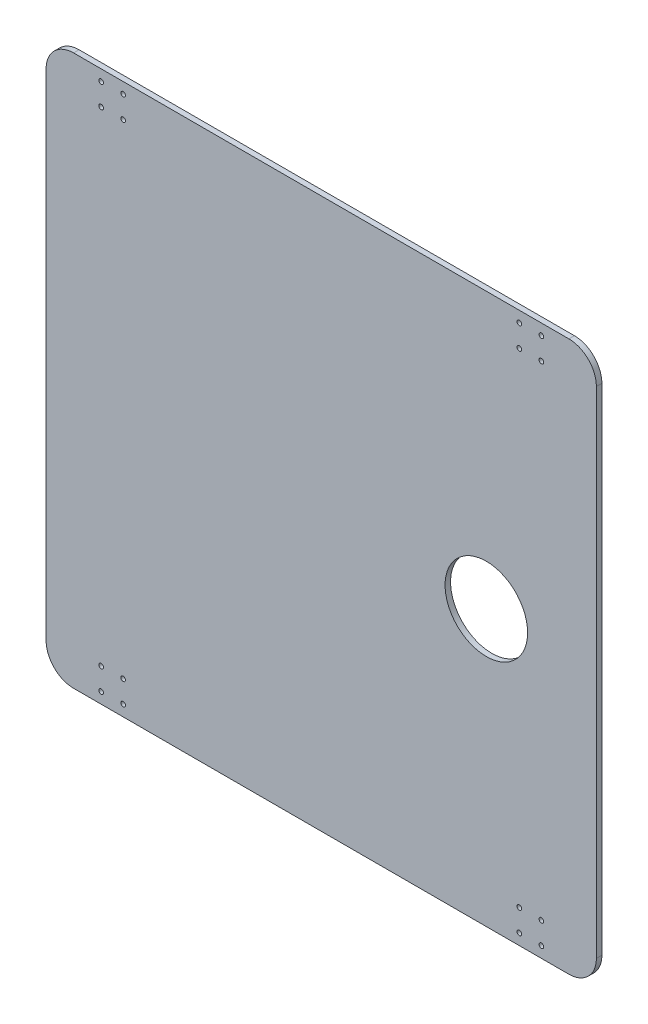
SolidWorks part; units mm, degrees
ref_plane "前视基准面" through (0, 0, 0) normal (0, 0, 1) x (1, 0, 0)
ref_plane "上视基准面" through (0, 0, 0) normal (0, 1, 0) x (1, 0, 0)
ref_plane "右视基准面" through (0, 0, 0) normal (1, 0, 0) x (0, 0, -1)
other "Configuration Table"
sketch "草图1" plane through (0, 0, 0) normal (0, 0, 1) x (1, 0, 0)
  line L0 (-492.228, -500) -> (1922.2798, -500) construction
  line L5 (0, 0) -> (1000, 0)
  line L6 (0, 0) -> (0, -1000)
  line L7 (0, -1000) -> (1000, -1000)
  line L8 (1000, 0) -> (1000, -1000)
  line L9 (500, 163.0817) -> (500, -1417.2292) construction
  line L10 (-171.3011, -40) -> (1184.3545, -40) construction
  circle A0 centre (800, -500) radius 75
  circle A1 centre (900, -20) radius 4.25
  circle A2 centre (900, -60) radius 4.25
  circle A3 centre (860, -20) radius 4.25
  circle A4 centre (860, -60) radius 4.25
  circle A5 centre (140, -20) radius 4.25
  circle A6 centre (100, -20) radius 4.25
  circle A7 centre (140, -60) radius 4.25
  circle A8 centre (100, -60) radius 4.25
  circle A9 centre (100, -980) radius 4.25
  circle A10 centre (140, -980) radius 4.25
  circle A11 centre (100, -940) radius 4.25
  circle A12 centre (140, -940) radius 4.25
  circle A13 centre (860, -980) radius 4.25
  circle A14 centre (900, -980) radius 4.25
  circle A15 centre (860, -940) radius 4.25
  circle A16 centre (900, -940) radius 4.25
  point P21 (0, 0)
  dimension "D3" = 150
  dimension "D6" = 8.5
  dimension "D7" = 40
  dimension "D1" = 1000
  dimension "D2" = 1000
  dimension "D4" = 300
  dimension "D5" = 40
  dimension "D8" = 100
  dimension "D9" = 40
  dimension "D10" = 40
extrude "凸台-拉伸1" add sketch "草图1" along normal blind 10
fillet "圆角1" radius 50 4 edges at (0, -1000, 5) (1000, -1000, 5) (1000, 0, 5) (0, 0, 5)
